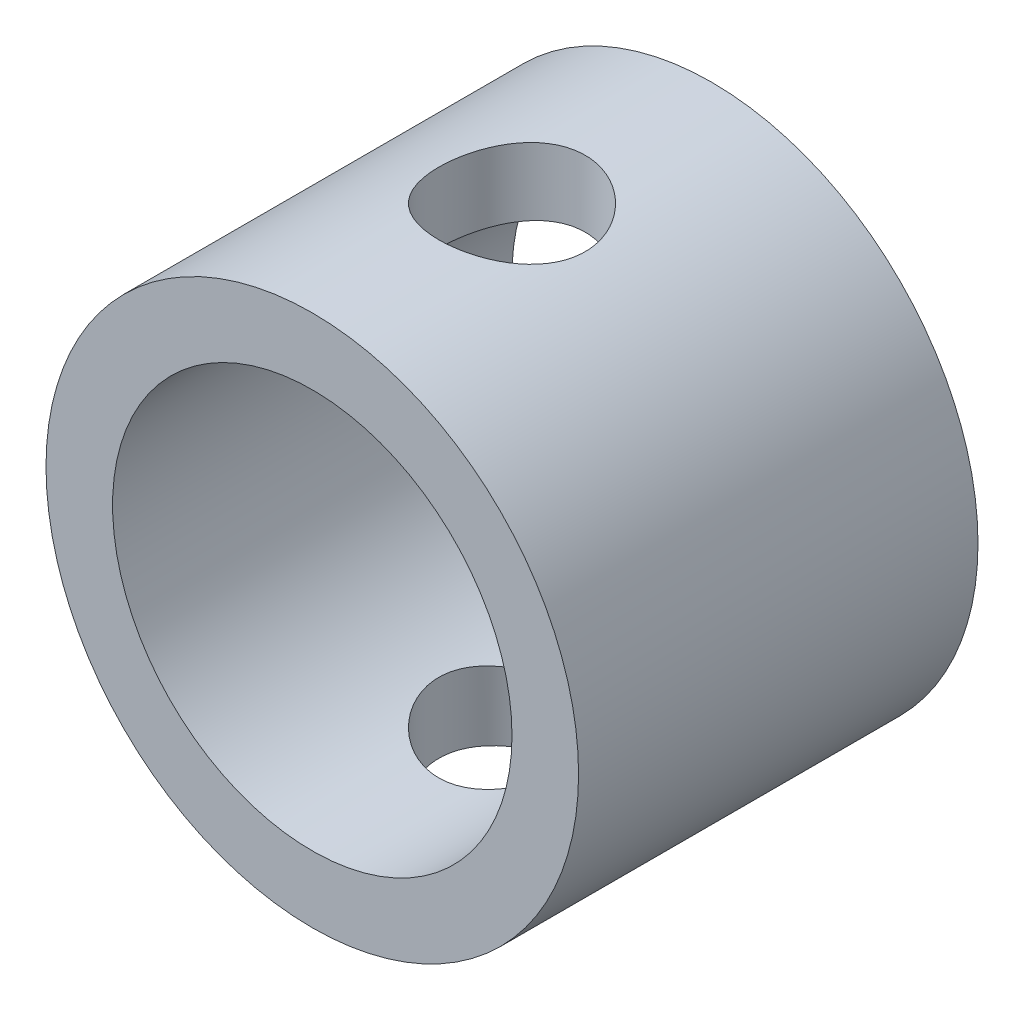
SolidWorks part; units mm, degrees
material "AISI 1020"
ref_plane "Ön Düzlem" through (0, 0, 0) normal (0, 0, 1) x (1, 0, 0)
ref_plane "Üst Düzlem" through (0, 0, 0) normal (0, 1, 0) x (1, 0, 0)
ref_plane "Sağ Düzlem" through (0, 0, 0) normal (1, 0, 0) x (0, 0, -1)
sketch "Çizim1" plane through (0, 0, 0) normal (0, 0, 1) x (1, 0, 0)
  circle A0 centre (0, 0) radius 40
  circle A1 centre (0, 0) radius 30
  dimension "D1" = 60
  dimension "D2" = 80
extrude "Yükseklik-Ekstrüzyon1" add sketch "Çizim1" along normal blind 60
sketch "Çizim2" plane through (0, 0, 0) normal (0, 1, 0) x (1, 0, 0)
  line L0 (30, 0) -> (-30, 0) construction
  circle A0 centre (0, -30) radius 11
  dimension "D1" = 22
  dimension "D2" = 30
extrude "Kes-Ekstrüzyon1" cut sketch "Çizim2" against normal mid plane 160
